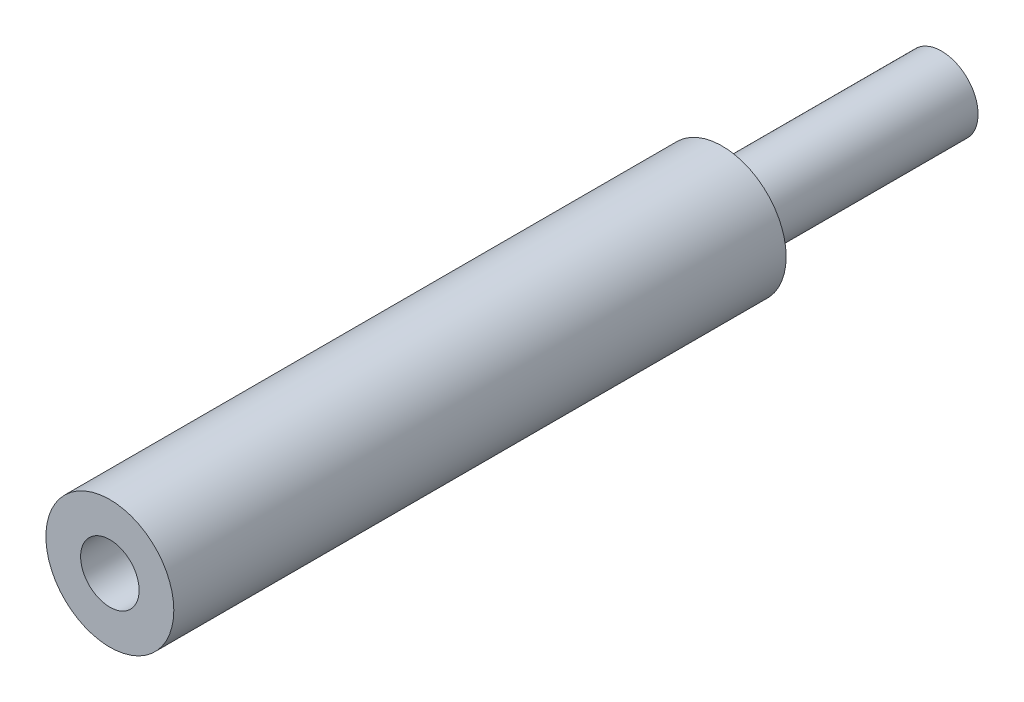
SolidWorks part; units mm, degrees
ref_plane "Front Plane" through (0, 0, 0) normal (0, 0, 1) x (1, 0, 0)
ref_plane "Top Plane" through (0, 0, 0) normal (0, 1, 0) x (1, 0, 0)
ref_plane "Right Plane" through (0, 0, 0) normal (1, 0, 0) x (0, 0, -1)
sketch "Sketch1" plane through (0, 0, 0) normal (0, 0, 1) x (1, 0, 0)
  circle A0 centre (0, 0) radius 3.5
  dimension "D1" = 7
extrude "Boss-Extrude1" add sketch "Sketch1" along normal blind 33.5
sketch "Sketch2" plane through (0, 0, 0) normal (0, 0, -1) x (-1, 0, 0)
  circle A0 centre (0, 0) radius 2
  dimension "D1" = 4
extrude "Boss-Extrude2" add sketch "Sketch2" along normal blind 12
hole_wizard "Tap Drill for M3 Tap1" positions "Sketch3" profile "Sketch4" hole size "M3" standard "IS"
sketch "Sketch3" plane through (0, 0, 33.5) normal (0, 0, 1) x (1, 0, 0)
  point P0 (0, 0)
sketch "Sketch4" plane through (0, 0, 33.5) normal (1, 0, 0) x (0, -1, 0)
  line L0 (0, 0) -> (0, 14.9614)
  line L1 (0, 14.9614) -> (1.6, 14)
  line L2 (1.6, 14) -> (1.6, 0)
  line L5 (1.6, 0) -> (0, 0)
  line L10 (0, 14.9614) -> (-1.6, 14) construction
  line L11 (0, -6.35) -> (0, 107.95) construction
  dimension "Hole Dia." = 3.2
  dimension "Hole Depth" = 14
  dimension "Drill Angle" = 118
ref_plane "Plane1" through (0, 3.5, 0) normal (0, 1, 0) x (1, 0, 0)
